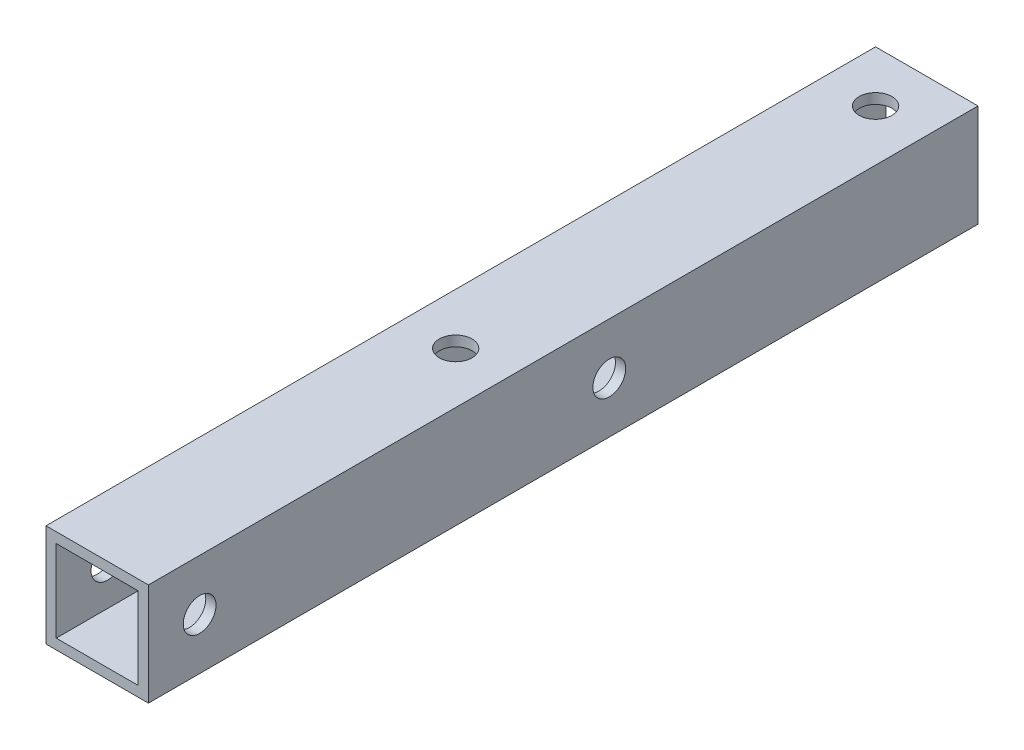
SolidWorks part; units mm, degrees
material "1060 合金"
ref_plane "正面" through (0, 0, 0) normal (0, 0, 1) x (1, 0, 0)
ref_plane "平面" through (0, 0, 0) normal (0, 1, 0) x (1, 0, 0)
ref_plane "右側面" through (0, 0, 0) normal (1, 0, 0) x (0, 0, -1)
sketch "ｽｹｯﾁ1" plane through (0, 0, 0) normal (0, 0, 1) x (1, 0, 0)
  line L1 (5, 5) -> (-5, 5)
  line L2 (5, 5) -> (5, -5)
  line L3 (5, -5) -> (-5, -5)
  line L4 (-5, 5) -> (-5, -5)
  line L5 (5, 5) -> (-5, -5) construction
  line L6 (5, -5) -> (-5, 5) construction
  point P0 (0, 0)
  dimension "D1" = 10
extrude "押し出し-薄板1" add sketch "ｽｹｯﾁ1" along normal blind 51 thin thin type one direction reverse wall 1
sketch "ｽｹｯﾁ2" plane through (5, 0, 0) normal (1, 0, 0) x (0, 0, -1)
  line L0 (-51, 0) -> (0, 0) construction
  line L1 (-51, -5) -> (-51, 5) construction
  circle A0 centre (-36, 0) radius 1.6
  dimension "D1" = 15
  dimension "D2" = 3.2
extrude "ｶｯﾄ - 押し出し1" cut sketch "ｽｹｯﾁ2" against normal through all
sketch "ｽｹｯﾁ3" plane through (0, 5, 0) normal (0, 1, 0) x (1, 0, 0)
  line L0 (0, 0) -> (0, -51) construction
  line L1 (5, -51) -> (-5, -51) construction
  line L2 (5, 0) -> (-5, 0) construction
  circle A0 centre (0, -46) radius 1.6
  circle A1 centre (0, -5) radius 1.6
  dimension "D1" = 3.2
  dimension "D2" = 41
  dimension "D3" = 5
  dimension "D4" = 3.2
extrude "ｶｯﾄ - 押し出し2" cut sketch "ｽｹｯﾁ3" against normal blind 10
sketch "ｽｹｯﾁ4" plane through (0, 0, 51) normal (0, 0, 1) x (1, 0, 0)
  line L1 (5, 5) -> (-5, 5)
  line L2 (5, 5) -> (5, -5)
  line L3 (5, -5) -> (-5, -5)
  line L4 (-5, 5) -> (-5, -5)
  line L5 (5, 5) -> (-5, -5) construction
  line L6 (5, -5) -> (-5, 5) construction
  line L7 (4, 4) -> (-4, 4)
  line L8 (4, 4) -> (4, -4)
  line L9 (4, -4) -> (-4, -4)
  line L10 (-4, 4) -> (-4, -4)
  line L11 (4, 4) -> (-4, -4) construction
  line L12 (4, -4) -> (-4, 4) construction
  point P0 (0, 0)
  point P7 (0, 0)
extrude "ﾎﾞｽ - 押し出し1" add sketch "ｽｹｯﾁ4" along normal blind 30
sketch "ｽｹｯﾁ5" plane through (5, 0, 0) normal (1, 0, 0) x (0, 0, -1)
  line L0 (-81, 0) -> (0, 0) construction
  line L1 (-81, -5) -> (-81, 5) construction
  circle A0 centre (-76, 0) radius 1.6
  dimension "D1" = 3.2
  dimension "D2" = 5
extrude "ｶｯﾄ - 押し出し3" cut sketch "ｽｹｯﾁ5" against normal through all
